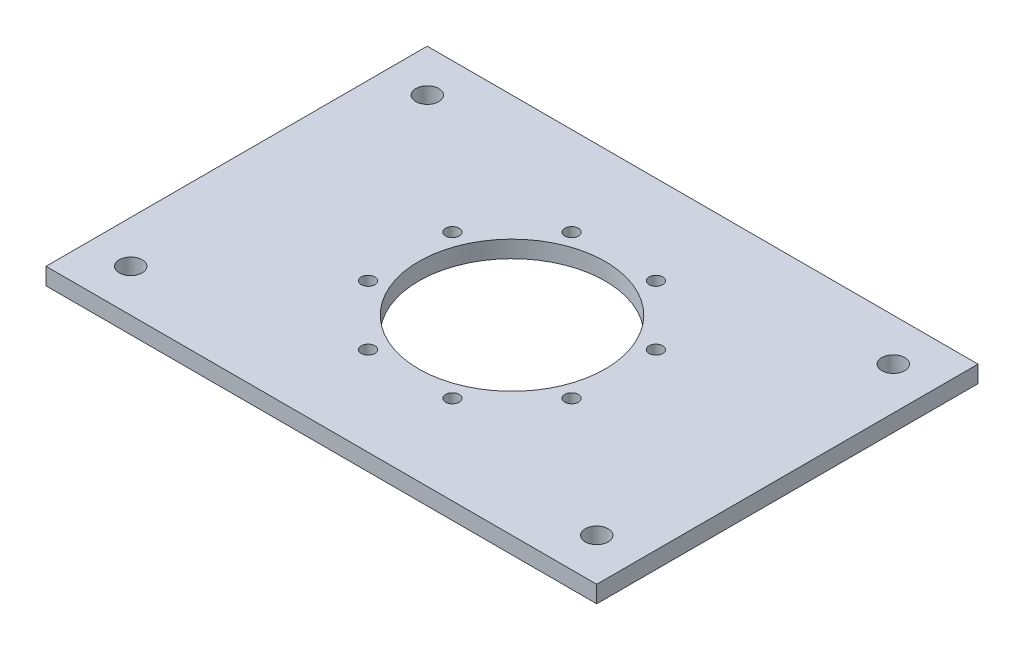
SolidWorks part; units mm, degrees
material "Plain Carbon Steel"
ref_plane "Front Plane" through (0, 0, 0) normal (0, 0, 1) x (1, 0, 0)
ref_plane "Top Plane" through (0, 0, 0) normal (0, 1, 0) x (1, 0, 0)
ref_plane "Right Plane" through (0, 0, 0) normal (1, 0, 0) x (0, 0, -1)
sketch "Sketch1" plane through (0, 0, 0) normal (0, 1, 0) x (1, 0, 0)
  line L1 (-162.5, -112.5) -> (162.5, -112.5)
  line L2 (-162.5, -112.5) -> (-162.5, 112.5)
  line L3 (-162.5, 112.5) -> (162.5, 112.5)
  line L4 (162.5, -112.5) -> (162.5, 112.5)
  line L5 (-162.5, -112.5) -> (162.5, 112.5) construction
  line L6 (-162.5, 112.5) -> (162.5, -112.5) construction
  circle A0 centre (0, 0) radius 55
  point P0 (0, 0)
  dimension "D3" = 110
  dimension "D1" = 225
  dimension "D2" = 325
extrude "Boss-Extrude1" add sketch "Sketch1" along normal blind 10
sketch "Sketch2" plane through (0, 0, 0) normal (0, 1, 0) x (1, 0, 0)
  line L0 (-24.8744, -60.0522) -> (0, 0) construction
  line L1 (0, -55) -> (0, 55) construction
  circle A0 centre (0, 0) radius 65 construction
  circle A1 centre (-24.8744, -60.0522) radius 4
  circle A2 centre (-60.0522, -24.8744) radius 4
  circle A3 centre (-60.0522, 24.8744) radius 4
  circle A4 centre (-24.8744, 60.0522) radius 4
  circle A5 centre (24.8744, 60.0522) radius 4
  circle A6 centre (60.0522, 24.8744) radius 4
  circle A7 centre (60.0522, -24.8744) radius 4
  circle A8 centre (24.8744, -60.0522) radius 4
  point P23 (0, 0)
  dimension "D1" = 130
  dimension "D2" = 8
  dimension "D3" = 22.5
extrude "Cut-Extrude1" cut sketch "Sketch2" along normal blind 10
sketch "Sketch3" plane through (0, 0, 112.5) normal (0, 0, 1) x (1, 0, 0)
  line L1 (-162.5, 10) -> (162.5, 10)
  line L2 (-162.5, 10) -> (-162.5, 0)
  line L3 (-162.5, 0) -> (162.5, 0)
  line L4 (162.5, 10) -> (162.5, 0)
extrude "Boss-Extrude2" [suppressed] add sketch "Sketch3" along normal blind 170
sketch "Sketch4" plane through (0, 0, 0) normal (0, 1, 0) x (1, 0, 0)
  line L2 (0, -5.5) -> (0, 5.5) construction
  line L3 (-5.5, 0) -> (5.5, 0) construction
  circle A0 centre (137.5, 87.5) radius 6.75
  circle A6 centre (-137.5, 87.5) radius 6.75
  circle A7 centre (137.5, -187.5) radius 6.75 [skipped]
  circle A8 centre (-137.5, -187.5) radius 6.75 [skipped]
  circle A9 centre (-137.5, -87.5) radius 6.75
  circle A10 centre (137.5, -87.5) radius 6.75
  point P6 (0, 0)
  point P15 (0, 25)
  point P16 (0, -50)
  dimension "D1" = 13.5
  dimension "D2" = 137.5
  dimension "D3" = 87.5
  dimension "D4" = 4
extrude "Cut-Extrude2" cut sketch "Sketch4" along normal up to next
